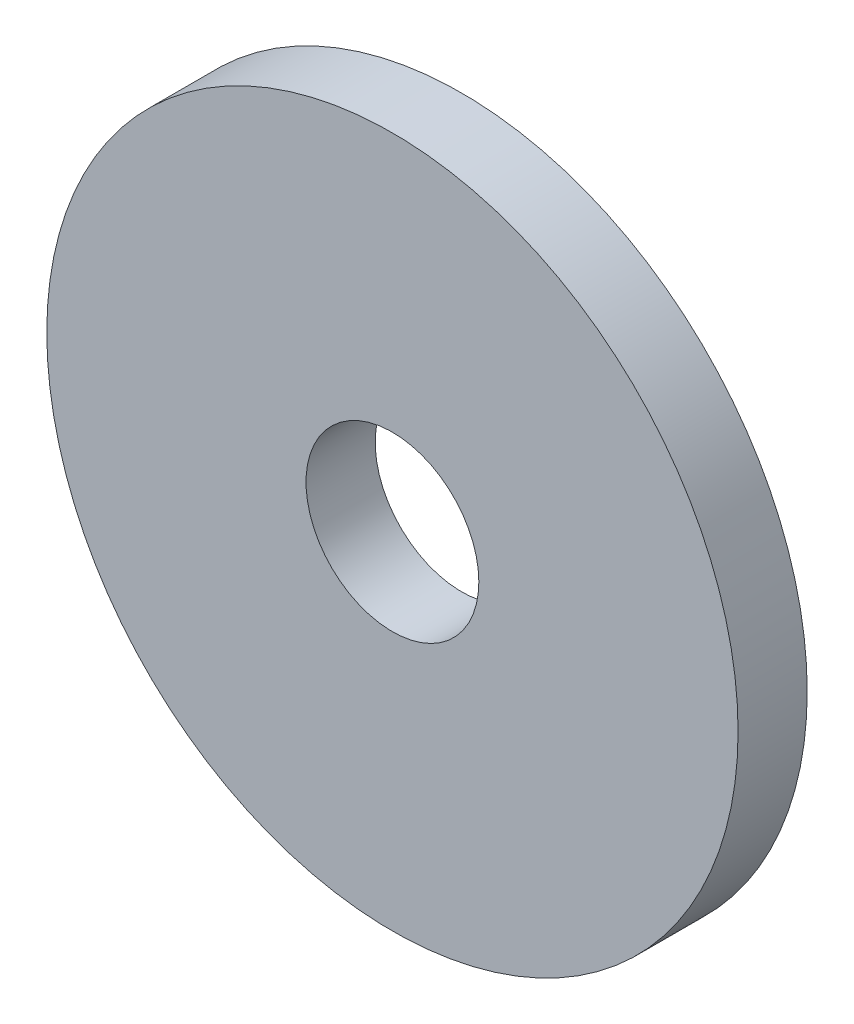
SolidWorks part; units mm, degrees
material "环氧树脂,未充填"
ref_plane "前视基准面" through (0, 0, 0) normal (0, 0, 1) x (1, 0, 0)
ref_plane "上视基准面" through (0, 0, 0) normal (0, 1, 0) x (1, 0, 0)
ref_plane "右视基准面" through (0, 0, 0) normal (1, 0, 0) x (0, 0, -1)
sketch "草图1" plane through (0, 0, 0) normal (0, 0, 1) x (1, 0, 0)
  circle A0 centre (0, 0) radius 10
  dimension "D1" = 20
extrude "凸台-拉伸1" add sketch "草图1" along normal blind 2
sketch "草图2" plane through (0, 0, 2) normal (0, 0, 1) x (1, 0, 0)
  circle A0 centre (0, 0) radius 2.5
  dimension "D1" = 5
extrude "切除-拉伸1" cut sketch "草图2" against normal through all
